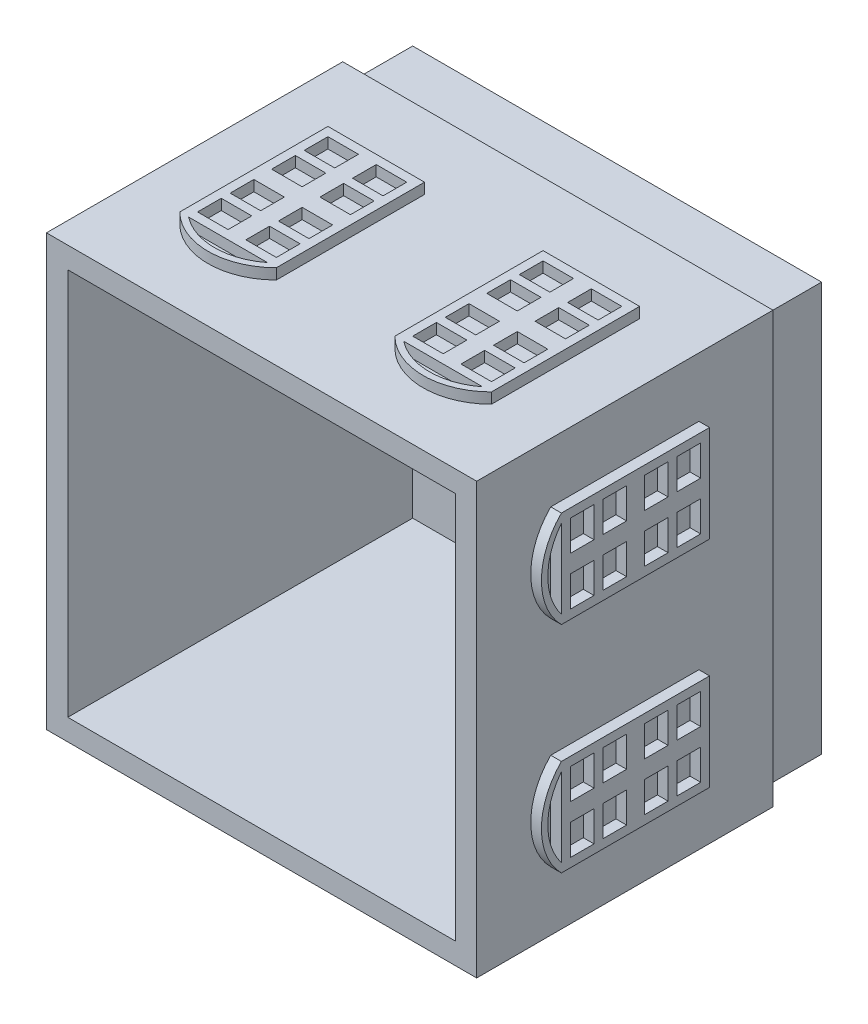
SolidWorks part; units mm, degrees
ref_plane "Alzado" through (0, 0, 0) normal (0, 0, 1) x (1, 0, 0)
ref_plane "Planta" through (0, 0, 0) normal (0, 1, 0) x (1, 0, 0)
ref_plane "Vista lateral" through (0, 0, 0) normal (1, 0, 0) x (0, 0, -1)
sketch "Croquis1" plane through (0, 0, 0) normal (0, 0, 1) x (1, 0, 0)
  line L0 (-86.7955, -42.2067) -> (-88.5955, -44.0067)
  line L3 (-88.5955, -44.0067) -> (-19.5955, -44.0067)
  line L7 (-86.7955, -42.2067) -> (-21.3955, -42.2067)
  line L9 (-21.3955, -42.2067) -> (-19.5955, -44.0067)
  dimension "D1" = 69
  dimension "D2" = 65.4
  dimension "D6" = 1.8
extrude "Saliente-Extruir1" add sketch "Croquis1" along normal blind 10
sketch "Croquis2" plane through (0, 0, 10) normal (0, 0, 1) x (1, 0, 0)
  line L3 (-90.3955, -45.8067) -> (-17.7955, -45.8067)
  line L7 (-86.7955, -42.2067) -> (-21.3955, -42.2067)
  line L11 (-88.5955, -44.0067) -> (-19.5955, -44.0067) construction
  line L12 (-90.3955, -45.8067) -> (-86.7955, -42.2067)
  line L13 (-21.3955, -42.2067) -> (-17.7955, -45.8067)
  dimension "D4" = 1.8
extrude "Saliente-Extruir2" add sketch "Croquis2" along normal blind 50
sketch "Croquis4" plane through (0, -45.8067, 0) normal (0, -1, 0) x (1, 0, 0)
  line L0 (-90.3955, 35) -> (-17.7955, 35) construction
  line L1 (-90.3955, 60) -> (-90.3955, 10) construction
  line L2 (-17.7955, 60) -> (-17.7955, 10) construction
  line L3 (-54.0955, 35) -> (-54.0955, 45.6878) construction
  line L5 (-44.0955, 47.5) -> (-44.0955, 22.5)
  line L6 (-44.0955, 22.5) -> (-27.7955, 22.5)
  line L7 (-27.7955, 47.5) -> (-27.7955, 22.5)
  line L11 (-44.0955, 35) -> (-27.7955, 35) construction
  line L12 (-35.9455, 35) -> (-35.9455, 46.8786) construction
  line L13 (-42.5955, 36.5) -> (-37.4455, 36.5)
  line L14 (-37.4455, 36.5) -> (-37.4455, 40.5)
  line L15 (-37.4455, 40.5) -> (-42.5955, 40.5)
  line L16 (-42.5955, 42) -> (-37.4455, 42)
  line L17 (-37.4455, 42) -> (-37.4455, 46)
  line L18 (-37.4455, 46) -> (-42.5955, 46)
  line L19 (-42.5955, 33.5) -> (-37.4455, 33.5)
  line L20 (-37.4455, 33.5) -> (-37.4455, 29.5)
  line L21 (-37.4455, 29.5) -> (-42.5955, 29.5)
  line L22 (-42.5955, 28) -> (-37.4455, 28)
  line L23 (-37.4455, 28) -> (-37.4455, 24)
  line L24 (-37.4455, 24) -> (-42.5955, 24)
  line L25 (-42.5955, 46) -> (-42.5955, 42)
  line L26 (-42.5955, 40.5) -> (-42.5955, 36.5)
  line L27 (-42.5955, 28) -> (-42.5955, 24)
  line L28 (-42.5955, 33.5) -> (-42.5955, 29.5)
  line L29 (-29.2955, 33.5) -> (-29.2955, 29.5)
  line L30 (-29.2955, 28) -> (-29.2955, 24)
  line L31 (-29.2955, 40.5) -> (-29.2955, 36.5)
  line L32 (-29.2955, 46) -> (-29.2955, 42)
  line L33 (-34.4455, 24) -> (-29.2955, 24)
  line L34 (-34.4455, 28) -> (-34.4455, 24)
  line L35 (-29.2955, 28) -> (-34.4455, 28)
  line L36 (-34.4455, 29.5) -> (-29.2955, 29.5)
  line L37 (-34.4455, 33.5) -> (-34.4455, 29.5)
  line L38 (-29.2955, 33.5) -> (-34.4455, 33.5)
  line L39 (-34.4455, 46) -> (-29.2955, 46)
  line L40 (-34.4455, 42) -> (-34.4455, 46)
  line L41 (-29.2955, 42) -> (-34.4455, 42)
  line L42 (-34.4455, 40.5) -> (-29.2955, 40.5)
  line L43 (-34.4455, 36.5) -> (-34.4455, 40.5)
  line L44 (-29.2955, 36.5) -> (-34.4455, 36.5)
  line L45 (-42.5955, 47.5) -> (-29.2955, 47.5)
  line L46 (-72.2455, 35) -> (-72.2455, 46.8786) construction
  line L47 (-64.0955, 35) -> (-80.3955, 35) construction
  line L48 (-65.5955, 47.5) -> (-78.8955, 47.5)
  line L49 (-78.8955, 36.5) -> (-73.7455, 36.5)
  line L50 (-73.7455, 36.5) -> (-73.7455, 40.5)
  line L51 (-73.7455, 40.5) -> (-78.8955, 40.5)
  line L52 (-78.8955, 42) -> (-73.7455, 42)
  line L53 (-73.7455, 42) -> (-73.7455, 46)
  line L54 (-73.7455, 46) -> (-78.8955, 46)
  line L55 (-78.8955, 33.5) -> (-73.7455, 33.5)
  line L56 (-73.7455, 33.5) -> (-73.7455, 29.5)
  line L57 (-73.7455, 29.5) -> (-78.8955, 29.5)
  line L58 (-78.8955, 28) -> (-73.7455, 28)
  line L59 (-73.7455, 28) -> (-73.7455, 24)
  line L60 (-73.7455, 24) -> (-78.8955, 24)
  line L61 (-78.8955, 46) -> (-78.8955, 42)
  line L62 (-78.8955, 40.5) -> (-78.8955, 36.5)
  line L63 (-78.8955, 28) -> (-78.8955, 24)
  line L64 (-78.8955, 33.5) -> (-78.8955, 29.5)
  line L65 (-65.5955, 33.5) -> (-65.5955, 29.5)
  line L66 (-65.5955, 28) -> (-65.5955, 24)
  line L67 (-65.5955, 40.5) -> (-65.5955, 36.5)
  line L68 (-65.5955, 46) -> (-65.5955, 42)
  line L69 (-70.7455, 24) -> (-65.5955, 24)
  line L70 (-70.7455, 28) -> (-70.7455, 24)
  line L71 (-65.5955, 28) -> (-70.7455, 28)
  line L72 (-70.7455, 29.5) -> (-65.5955, 29.5)
  line L73 (-70.7455, 33.5) -> (-70.7455, 29.5)
  line L74 (-65.5955, 33.5) -> (-70.7455, 33.5)
  line L75 (-70.7455, 46) -> (-65.5955, 46)
  line L76 (-70.7455, 42) -> (-70.7455, 46)
  line L77 (-65.5955, 42) -> (-70.7455, 42)
  line L78 (-70.7455, 40.5) -> (-65.5955, 40.5)
  line L79 (-70.7455, 36.5) -> (-70.7455, 40.5)
  line L80 (-65.5955, 36.5) -> (-70.7455, 36.5)
  line L81 (-80.3955, 47.5) -> (-80.3955, 22.5)
  line L82 (-64.0955, 22.5) -> (-80.3955, 22.5)
  line L83 (-64.0955, 47.5) -> (-64.0955, 22.5)
  arc A0 (-44.0955, 47.5) -> (-27.7955, 47.5) centre (-35.9455, 39.35) cw
  arc A1 (-42.5955, 47.5) -> (-29.2955, 47.5) centre (-35.9455, 39.0202) cw
  arc A2 (-65.5955, 47.5) -> (-78.8955, 47.5) centre (-72.2455, 39.0202) ccw
  arc A3 (-64.0955, 47.5) -> (-80.3955, 47.5) centre (-72.2455, 39.35) ccw
  dimension "D1" = 10
  dimension "D2" = 10
  dimension "D3" = 25
  dimension "D4" = 12.5
  dimension "D5" = 1.5
  dimension "D6" = 1.5
  dimension "D7" = 4
  dimension "D8" = 1.5
  dimension "D9" = 4
  dimension "D10" = 1.5
  dimension "D11" = 4
  dimension "D12" = 4
  dimension "D13" = 1.5
  dimension "D14" = 1.5
extrude "Saliente-Extruir3" add sketch "Croquis4" along normal blind 1.8
sketch "Croquis5" plane through (-27.7955, 0, 0) normal (1, 0, 0) x (0, 0, -1)
  line L3 (-22.5, -47.6067) -> (-22.5, -45.8067)
  line L4 (-22.5, -45.8067) -> (-20.7, -45.8067)
  line L5 (-20.7, -45.8067) -> (-22.5, -47.6067)
  dimension "D1" = 1.8
extrude "Saliente-Extruir4" add sketch "Croquis5" against normal up to vertex
sketch "Croquis12" plane through (0, 0, 60) normal (0, 0, 1) x (1, 0, 0)
  line L0 (-54.0955, -42.2067) -> (-54.0955, -9.5067) construction
  line L1 (-21.3955, -42.2067) -> (-86.7955, -42.2067) construction
  dimension "D1" = 32.7
ref_plane "Plano3" through (-54.0955, 0, 0) normal (1, 0, 0) x (0, 1, 0)
sketch "Croquis13" plane through (-54.0955, 0, 0) normal (1, 0, 0) x (0, 1, 0)
  line L0 (-9.5067, 60) -> (-9.5067, 28.9934) construction
sketch "Croquis14" plane through (-80.3955, 0, 0) normal (-1, 0, 0) x (0, 0, 1)
  line L0 (22.5, -47.6067) -> (22.5, -45.8067)
  line L1 (22.5, -45.8067) -> (20.7, -45.8067)
  line L2 (20.7, -45.8067) -> (22.5, -47.6067)
extrude "Saliente-Extruir5" add sketch "Croquis14" against normal up to vertex
pattern_circular "MatrizC5" count 4 every 90 about axis through (-54.0955, -9.5067, 0) along (0, 0, 1) of "Saliente-Extruir3", "Saliente-Extruir2", "Saliente-Extruir1"
sketch "Croquis16" plane through (0, 0, 0) normal (0, 0, -1) x (-1, 0, 0)
  line L1 (86.7955, -42.2067) -> (21.3955, -42.2067)
  line L2 (86.7955, -42.2067) -> (86.7955, 23.1933)
  line L3 (86.7955, 23.1933) -> (21.3955, 23.1933)
  line L4 (21.3955, -42.2067) -> (21.3955, 23.1933)
extrude "Saliente-Extruir6" add sketch "Croquis16" against normal blind 1.8
